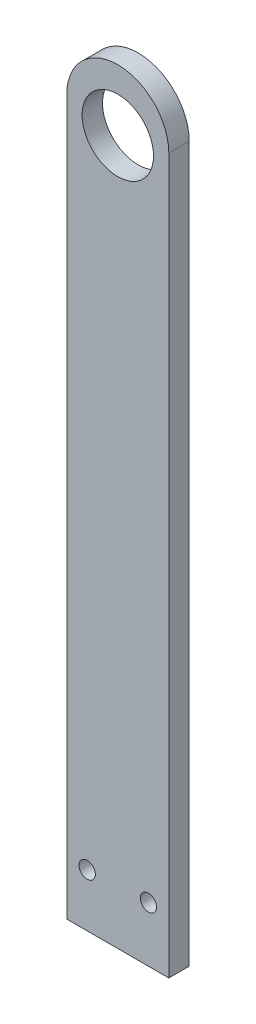
SolidWorks part; units mm, degrees
ref_plane "前基準面" through (0, 0, 0) normal (0, 0, 1) x (1, 0, 0)
ref_plane "上基準面" through (0, 0, 0) normal (0, 1, 0) x (1, 0, 0)
ref_plane "右基準面" through (0, 0, 0) normal (1, 0, 0) x (0, 0, -1)
sketch "草圖1" plane through (0, 0, 0) normal (0, 0, 1) x (1, 0, 0)
  line L1 (-10, 75) -> (10, 75)
  line L2 (-10, 75) -> (-10, -75)
  line L3 (-10, -75) -> (10, -75)
  line L4 (10, 75) -> (10, -75)
  line L5 (-10, 75) -> (10, -75) construction
  line L6 (-10, -75) -> (10, 75) construction
  point P0 (0, 0)
  dimension "D1" = 20
  dimension "D2" = 150
extrude "填料-伸長1" add sketch "草圖1" along normal blind 4
sketch "草圖2" plane through (0, 0, 4) normal (0, 0, 1) x (1, 0, 0)
  line L0 (0, 75) -> (0, -75) construction
  line L1 (10, 75) -> (-10, 75) construction
  line L2 (-10, -75) -> (10, -75) construction
  line L3 (-10, 65) -> (10, 65) construction
  line L4 (10, -75) -> (10, 75) construction
  line L5 (0, 75) -> (0, 57) construction
  line L6 (0, 75) -> (-10, 75)
  line L7 (-10, 75) -> (-10, 65)
  line L8 (0, 75) -> (10, 75)
  line L9 (10, 75) -> (10, 65)
  line L10 (-10, 75) -> (0, 75)
  arc A0 (10, 65) -> (-10, 65) centre (0, 65) ccw
  arc A1 (0, 75) -> (-10, 65) centre (0, 65) ccw
  line M2 (10, -75) -> (10, 75)
  line M3 (10, 75) -> (-10, 75)
  line M4 (-10, 75) -> (-10, -75)
extrude "除料-伸長1" cut sketch "草圖2" against normal blind 4 contours A0 M3 M4 | A0 M2 M3
sketch "草圖3" plane through (0, 0, 4) normal (0, 0, 1) x (1, 0, 0)
  line L0 (0, 75) -> (0, -75) construction
  line L1 (-10, -75) -> (10, -75) construction
  arc A0 (10, 65) -> (-10, 65) centre (0, 65) ccw construction
  circle A1 centre (0, 63) radius 7
  circle A2 centre (-6, -64.6324) radius 1.6
  circle A3 centre (6, -64.2022) radius 1.6
  point P13 (0, 0)
  dimension "D1" = 14
  dimension "D5" = 3.2
  dimension "D6" = 3.2
  dimension "D2" = 12
  dimension "D3" = 6
  dimension "D4" = 6
extrude "除料-伸長2" cut sketch "草圖3" against normal through all
